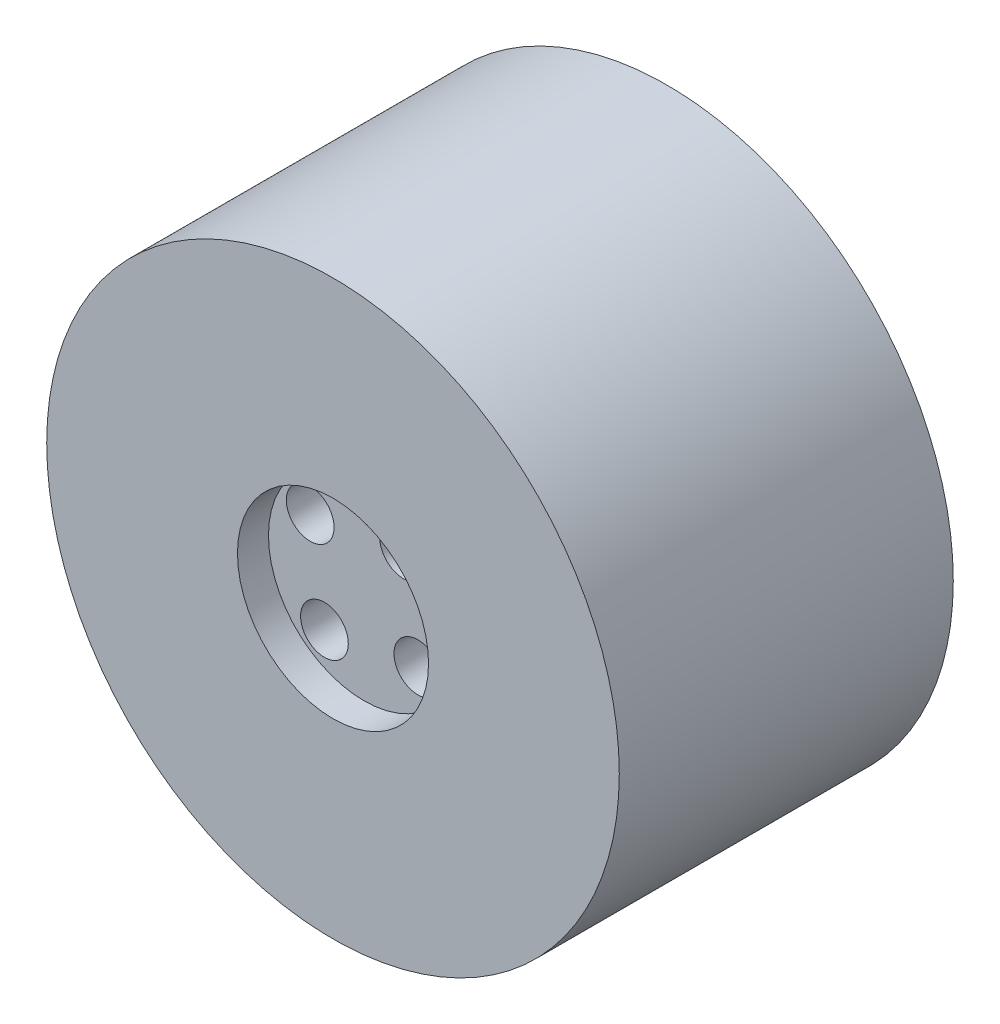
SolidWorks part; units mm, degrees
ref_plane "Front Plane" through (0, 0, 0) normal (0, 0, 1) x (1, 0, 0)
ref_plane "Top Plane" through (0, 0, 0) normal (0, 1, 0) x (1, 0, 0)
ref_plane "Right Plane" through (0, 0, 0) normal (1, 0, 0) x (0, 0, -1)
sketch "Sketch1" plane through (0, 0, 0) normal (0, 0, 1) x (1, 0, 0)
  circle A0 centre (0, 0) radius 60
extrude "Boss-Extrude1" add sketch "Sketch1" along normal blind 70
sketch "Sketch2" plane through (0, 0, 70) normal (0, 0, 1) x (1, 0, 0)
  circle A0 centre (0, 0) radius 20.02
extrude "Cut-Extrude1" cut sketch "Sketch2" against normal blind 6.5
sketch "Sketch3" plane through (0, 0, 0) normal (0, 0, -1) x (-1, 0, 0)
  circle A0 centre (0, 0) radius 20
extrude "Boss-Extrude2" add sketch "Sketch3" along normal blind 6
sketch "Sketch4" plane through (0, 0, 70) normal (0, 0, 1) x (1, 0, 0)
  circle A0 centre (-11.2783, 8.2945) radius 5
  point P2 (0, 0)
  dimension "D1" = 14
extrude "Cut-Extrude2" cut sketch "Sketch4" against normal through all
pattern_circular "CirPattern1" count 4 over 360 about axis through (0, 0, 0) along (0, 0, 1) of "Cut-Extrude2"
